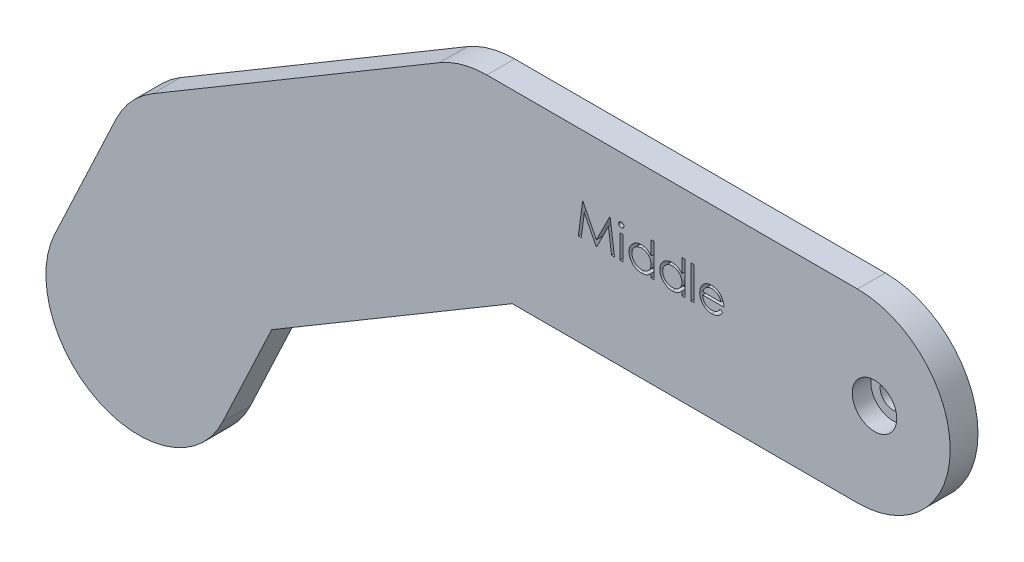
SolidWorks part; units mm, degrees
ref_plane "Front Plane" through (0, 0, 0) normal (0, 0, 1) x (1, 0, 0)
ref_plane "Top Plane" through (0, 0, 0) normal (0, 1, 0) x (1, 0, 0)
ref_plane "Right Plane" through (0, 0, 0) normal (1, 0, 0) x (0, 0, -1)
sketch "Sketch1" plane through (0, 0, 0) normal (0, 0, 1) x (1, 0, 0)
  line L0 (0, 0) -> (40, 0) construction
  line L2 (0, 10) -> (40, 10)
  line L3 (0, -10) -> (40, -10)
  arc A0 (0, 10) -> (0, -10) centre (0, 0) ccw
  arc A1 (40, -10) -> (40, 10) centre (40, 0) ccw
  point P5 (20, 0)
extrude "Boss-Extrude1" add sketch "Sketch1" along normal blind 3
sketch "Sketch2" plane through (0, 0, 0) normal (0, 0, 1) x (1, 0, 0)
  line L0 (0, 0) -> (-30.9572, -18.3753) construction
  line L2 (5.1043, -8.5992) -> (-25.8529, -26.9746)
  line L3 (-5.1043, 8.5992) -> (-36.0614, -9.7761)
  arc A0 (5.1043, -8.5992) -> (-5.1043, 8.5992) centre (0, 0) ccw
  arc A1 (-36.0614, -9.7761) -> (-25.8529, -26.9746) centre (-30.9572, -18.3753) ccw
  point P5 (-15.4786, -9.1877)
extrude "Boss-Extrude2" add sketch "Sketch2" along normal blind 3
sketch "Sketch3" plane through (0, 0, 0) normal (0, 0, 1) x (1, 0, 0)
  line L0 (-30.9572, -18.3753) -> (-37.5752, -32.4423) construction
  line L2 (-21.9086, -22.6324) -> (-28.5266, -36.6993)
  line L3 (-40.0058, -14.1183) -> (-46.6238, -28.1852)
  arc A0 (-21.9086, -22.6324) -> (-40.0058, -14.1183) centre (-30.9572, -18.3753) ccw
  arc A1 (-46.6238, -28.1852) -> (-28.5266, -36.6993) centre (-37.5752, -32.4423) ccw
  point P5 (-34.2662, -25.4088)
extrude "Boss-Extrude4" add sketch "Sketch3" along normal blind 3
sketch "Sketch4" plane through (0, 0, 0) normal (0, 0, 1) x (1, 0, 0)
  circle A0 centre (41.8354, 0) radius 1.4
extrude "Cut-Extrude5" cut sketch "Sketch4" along normal blind 3
sketch "Sketch5" plane through (0, 0, 3) normal (0, 0, 1) x (1, 0, 0)
  circle A0 centre (41.8354, 0) radius 2.4
extrude "Cut-Extrude6" cut sketch "Sketch5" against normal blind 2
sketch "Sketch7" plane through (0, 0, 3) normal (0, 0, 1) x (1, 0, 0)
  text T0 "Middle"
extrude "Cut-Extrude7" cut sketch "Sketch7" against normal blind 1
